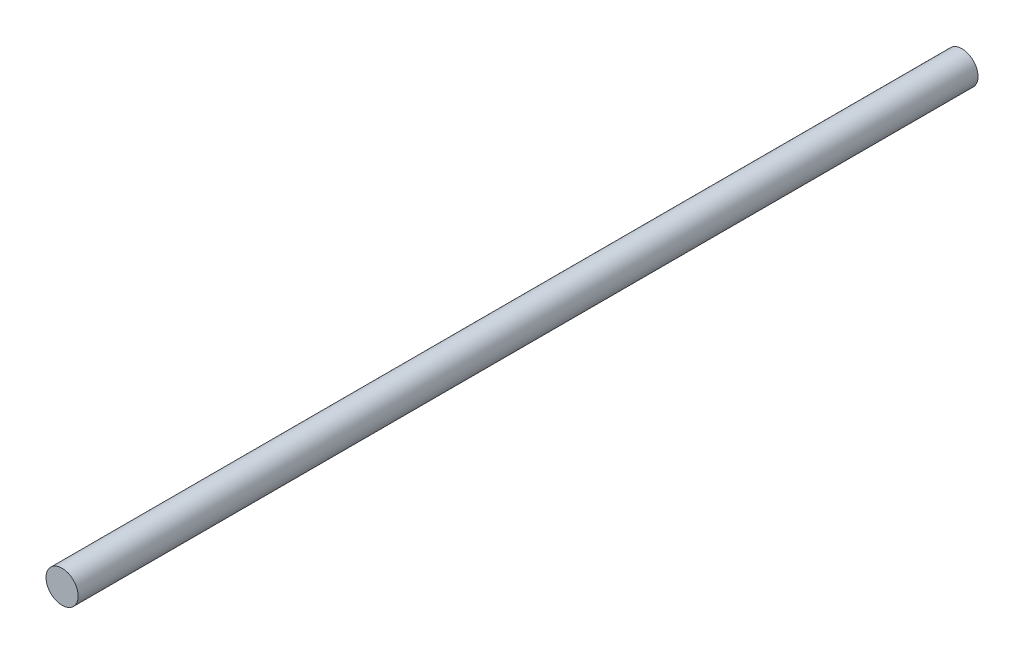
SolidWorks part; units mm, degrees
material "AISI 316 Stainless Steel Sheet (SS)"
ref_plane "Front Plane" through (0, 0, 0) normal (0, 0, 1) x (1, 0, 0)
ref_plane "Top Plane" through (0, 0, 0) normal (0, 1, 0) x (1, 0, 0)
ref_plane "Right Plane" through (0, 0, 0) normal (1, 0, 0) x (0, 0, -1)
sketch "Sketch1" plane through (0, 0, 0) normal (0, 0, 1) x (1, 0, 0)
  circle A0 centre (0, 0) radius 5
  dimension "D1" = 10
extrude "Boss-Extrude1" add sketch "Sketch1" along normal blind 280
